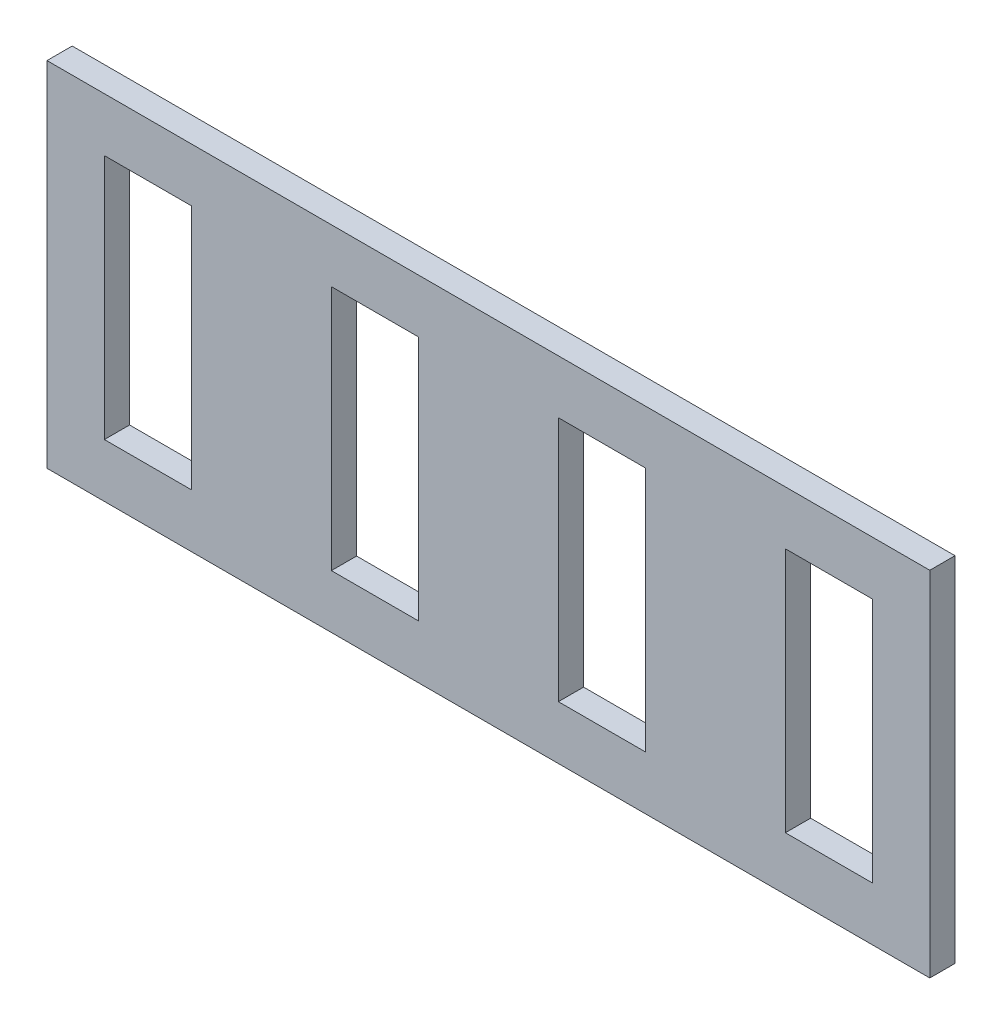
SolidWorks part; units mm, degrees
ref_plane "Front Plane" through (0, 0, 0) normal (0, 0, 1) x (1, 0, 0)
ref_plane "Top Plane" through (0, 0, 0) normal (0, 1, 0) x (1, 0, 0)
ref_plane "Right Plane" through (0, 0, 0) normal (1, 0, 0) x (0, 0, -1)
sketch "Sketch1" plane through (0, 0, 0) normal (0, 0, 1) x (1, 0, 0)
  line L0 (-455, 140) -> (245, 140)
  line L1 (245, 140) -> (245, -140)
  line L2 (245, -140) -> (-455, -140)
  line L3 (-455, -140) -> (-455, 140)
  line L4 (0, 239.2473) -> (0, -291.9355) construction
  line L5 (-436.5591, 0) -> (606.4516, 0) construction
  line L6 (-160.5, 97.5) -> (-160.5, -97.5)
  line L7 (-409.5, 97.5) -> (-340.5, 97.5)
  line L8 (-409.5, 97.5) -> (-409.5, -97.5)
  line L9 (-409.5, -97.5) -> (-340.5, -97.5)
  line L10 (-340.5, 97.5) -> (-340.5, -97.5)
  line L11 (-409.5, 97.5) -> (-340.5, -97.5) construction
  line L12 (-409.5, -97.5) -> (-340.5, 97.5) construction
  line L13 (-229.5, 97.5) -> (-160.5, 97.5)
  line L14 (-229.5, 97.5) -> (-229.5, -97.5)
  line L15 (-229.5, -97.5) -> (-160.5, -97.5)
  line L16 (19.5, 97.5) -> (19.5, -97.5)
  line L17 (-49.5, 97.5) -> (19.5, 97.5)
  line L18 (-49.5, 97.5) -> (-49.5, -97.5)
  line L19 (-49.5, -97.5) -> (19.5, -97.5)
  line L20 (199.5, 97.5) -> (199.5, -97.5)
  line L21 (130.5, 97.5) -> (199.5, 97.5)
  line L22 (130.5, 97.5) -> (130.5, -97.5)
  line L23 (130.5, -97.5) -> (199.5, -97.5)
  line L24 (-195, -47.5255) -> (-195, -194.988) construction
  point P9 (-375, 0)
  dimension "D1" = 700
  dimension "D2" = 280
  dimension "D3" = 140
  dimension "D4" = 69
  dimension "D5" = 195
  dimension "D6" = 80
  dimension "D8" = 34.5
  dimension "D9" = 180
  dimension "D7" = 4
extrude "Boss-Extrude1" add sketch "Sketch1" along normal blind 20
